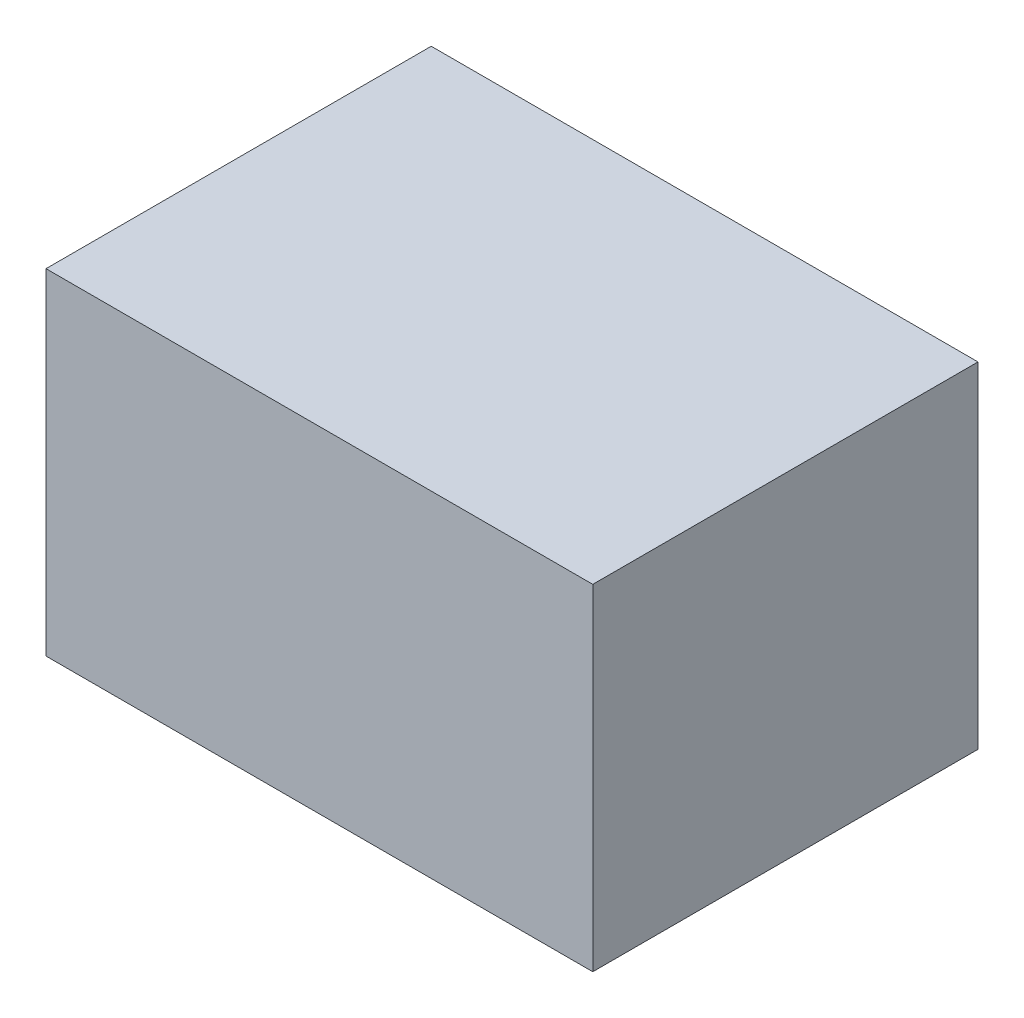
SolidWorks part; units mm, degrees
ref_plane "Front Plane" through (0, 0, 0) normal (0, 0, 1) x (1, 0, 0)
ref_plane "Top Plane" through (0, 0, 0) normal (0, 1, 0) x (1, 0, 0)
ref_plane "Right Plane" through (0, 0, 0) normal (1, 0, 0) x (0, 0, -1)
sketch "Sketch1" plane through (0, 0, 0) normal (0, 0, 1) x (1, 0, 0)
  line L1 (-11, -6.75) -> (11, -6.75)
  line L2 (-11, -6.75) -> (-11, 6.75)
  line L3 (-11, 6.75) -> (11, 6.75)
  line L4 (11, -6.75) -> (11, 6.75)
  line L5 (-11, -6.75) -> (11, 6.75) construction
  line L6 (-11, 6.75) -> (11, -6.75) construction
  point P0 (0, 0)
extrude "Envelope" add sketch "Sketch1" along normal blind 15.5
